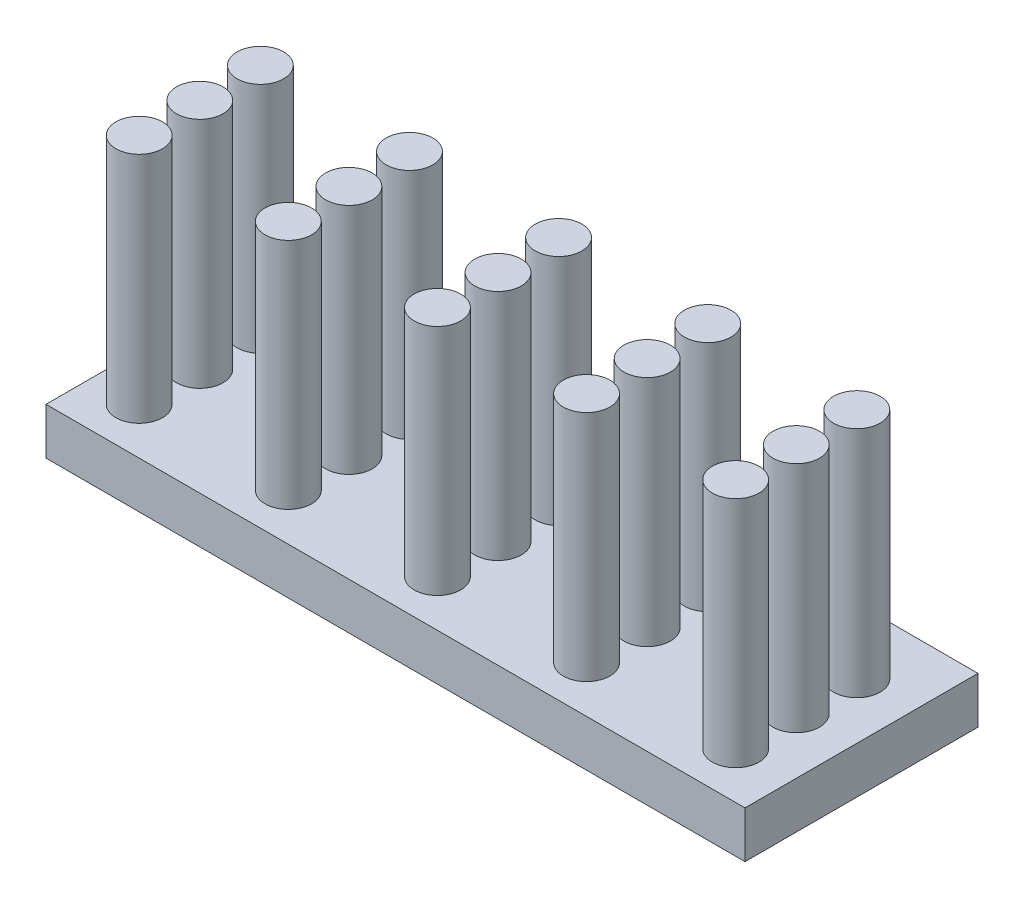
SolidWorks part; units mm, degrees
ref_plane "Plan de face" through (0, 0, 0) normal (0, 0, 1) x (1, 0, 0)
ref_plane "Plan de dessus" through (0, 0, 0) normal (0, 1, 0) x (1, 0, 0)
ref_plane "Plan de droite" through (0, 0, 0) normal (1, 0, 0) x (0, 0, -1)
sketch "Esquisse1" plane through (0, 0, 0) normal (0, 1, 0) x (1, 0, 0)
  line L1 (-75, 25) -> (75, 25)
  line L2 (-75, 25) -> (-75, -25)
  line L3 (-75, -25) -> (75, -25)
  line L4 (75, 25) -> (75, -25)
  line L5 (-75, 25) -> (75, -25) construction
  line L6 (-75, -25) -> (75, 25) construction
  point P0 (0, 0)
  dimension "D1" = 50
  dimension "D2" = 150
extrude "Boss.-Extru.1" add sketch "Esquisse1" along normal blind 10
sketch "Esquisse2" plane through (0, 10, 0) normal (0, 1, 0) x (1, 0, 0)
  line L0 (-75, -25) -> (75, -25) construction
  line L3 (-75, 25) -> (-75, -25) construction
  circle A0 centre (-65, -15) radius 5
  point P6 (-75, -15.4503)
  point P7 (-75, -21.117)
  dimension "D3" = 10
  dimension "D1" = 10
  dimension "D2" = 10
extrude "Boss.-Extru.2" add sketch "Esquisse2" along normal blind 50
pattern_linear "Répétition linéaire1" count 5 spacing 32 along (1, 0, 0) count 3 spacing 13 along (0, 0, -1) of "Boss.-Extru.2"
